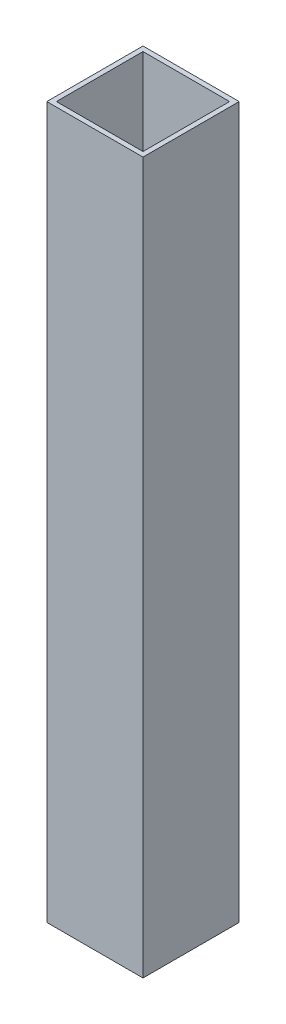
SolidWorks part; units mm, degrees
ref_plane "Front Plane" through (0, 0, 0) normal (0, 0, 1) x (1, 0, 0)
ref_plane "Top Plane" through (0, 0, 0) normal (0, 1, 0) x (1, 0, 0)
ref_plane "Right Plane" through (0, 0, 0) normal (1, 0, 0) x (0, 0, -1)
sketch "Sketch1" plane through (0, 0, 0) normal (0, 1, 0) x (1, 0, 0)
  line L1 (-10, 10) -> (10, 10)
  line L2 (-10, 10) -> (-10, -10)
  line L3 (-10, -10) -> (10, -10)
  line L4 (10, 10) -> (10, -10)
  line L5 (-10, 10) -> (10, -10) construction
  line L6 (-10, -10) -> (10, 10) construction
  line L7 (-9, 9) -> (9, 9)
  line L8 (-9, 9) -> (-9, -9)
  line L9 (-9, -9) -> (9, -9)
  line L10 (9, 9) -> (9, -9)
  line L11 (-9, 9) -> (9, -9) construction
  line L12 (-9, -9) -> (9, 9) construction
  point P0 (0, 0)
  point P6 (0, 0)
  dimension "D1" = 20
  dimension "D2" = 20
  dimension "D3" = 18
  dimension "D4" = 18
extrude "Boss-Extrude1" add sketch "Sketch1" along normal blind 147.8
